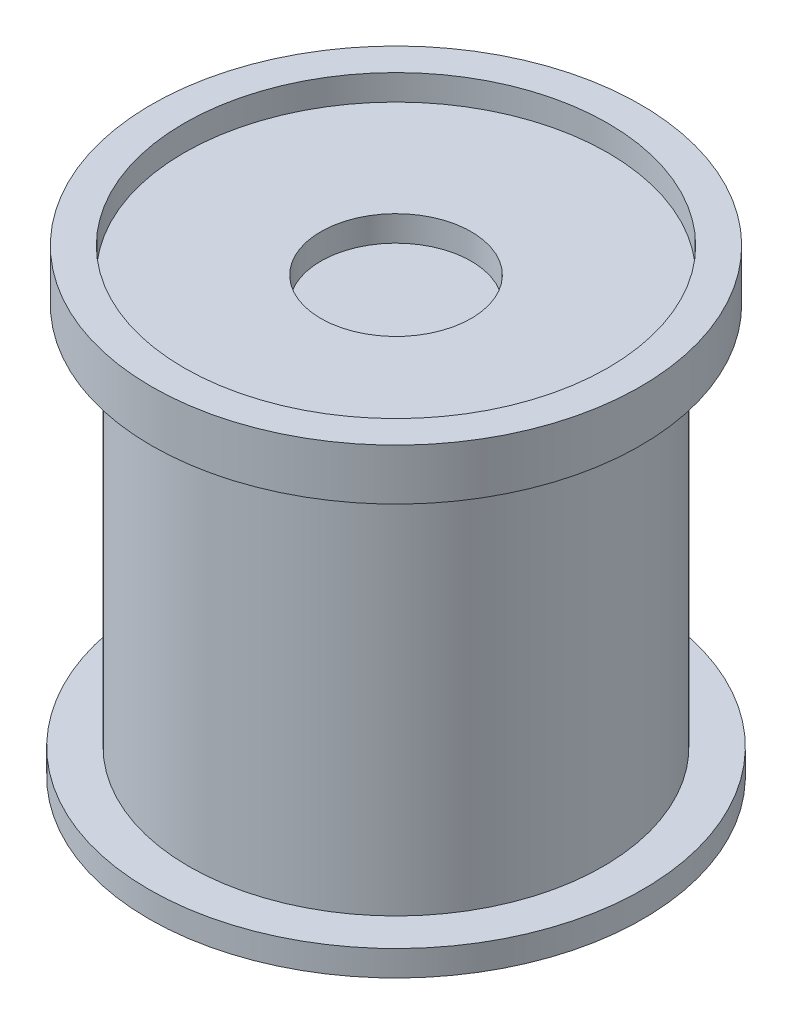
SolidWorks part; units mm, degrees
ref_plane "Front Plane" through (0, 0, 0) normal (0, 0, 1) x (1, 0, 0)
ref_plane "Top Plane" through (0, 0, 0) normal (0, 1, 0) x (1, 0, 0)
ref_plane "Right Plane" through (0, 0, 0) normal (1, 0, 0) x (0, 0, -1)
sketch "Sketch1" plane through (0, 0, 0) normal (0, 1, 0) x (1, 0, 0)
  circle A0 centre (0, 0) radius 9.6733
extrude "Boss-Extrude1" add sketch "Sketch1" along normal blind 1
sketch "Sketch2" plane through (0, 1, 0) normal (0, 1, 0) x (1, 0, 0)
  circle A0 centre (0, 0) radius 8.1126
extrude "Boss-Extrude2" add sketch "Sketch2" along normal blind 15
sketch "Sketch3" plane through (0, 16, 0) normal (0, 1, 0) x (1, 0, 0)
  circle A0 centre (0, 0) radius 9.5721
extrude "Boss-Extrude3" add sketch "Sketch3" along normal blind 2
sketch "Sketch4" plane through (0, 18, 0) normal (0, 1, 0) x (1, 0, 0)
  circle A0 centre (0, 0) radius 8.2981
extrude "Cut-Extrude2" cut sketch "Sketch4" against normal blind 1
sketch "Sketch5" plane through (0, 17, 0) normal (0, 1, 0) x (1, 0, 0)
  circle A0 centre (0, 0) radius 2.9456
extrude "Cut-Extrude3" cut sketch "Sketch5" against normal blind 1
